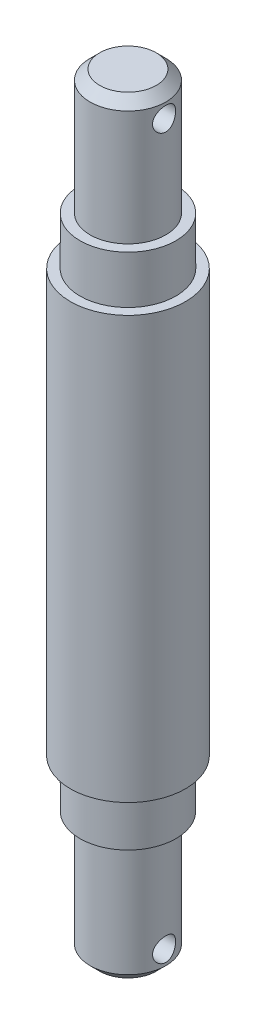
SolidWorks part; units mm, degrees
ref_plane "Plano frontal" through (0, 0, 0) normal (0, 0, 1) x (1, 0, 0)
ref_plane "Plano superior" through (0, 0, 0) normal (0, 1, 0) x (1, 0, 0)
ref_plane "Plano direito" through (0, 0, 0) normal (1, 0, 0) x (0, 0, -1)
sketch "Esboço1" plane through (0, 0, 0) normal (0, 1, 0) x (1, 0, 0)
  circle A0 centre (0, 0) radius 6
  dimension "D1" = 12
extrude "Ressalto-extrusão1" add sketch "Esboço1" along normal blind 44
sketch "Esboço2" plane through (0, 0, 0) normal (0, -1, 0) x (-1, 0, 0)
  circle A0 centre (0, 0) radius 5
  dimension "D1" = 10
extrude "Ressalto-extrusão3" add sketch "Esboço2" against normal blind 49 and the other way blind 5 contours A0
sketch "Esboço3" plane through (0, 49, 0) normal (0, 1, 0) x (1, 0, 0)
  circle A0 centre (0, 0) radius 3.95
  dimension "D1" = 7.9
extrude "Ressalto-extrusão4" add sketch "Esboço3" along normal blind 13 and the other way blind 67
chamfer "Chanfro1" distance 1 angle 45 1 edges at (0, 62, 3.95)
chamfer "Chanfro2" distance 1 angle 45 1 edges at (0, -18, 3.95)
sketch "Esboço5" plane through (0, 0, 0) normal (1, 0, 0) x (0, 0, -1)
  line L0 (2.95, 62) -> (-2.95, 62) construction
  line L1 (0, 61) -> (0, 57.6049) construction
  line L2 (-3.95, 61) -> (3.95, 61) construction
  circle A0 centre (0, 59.5) radius 1.2
  dimension "D1" = 2.4
  dimension "D2" = 2.5
extrude "Corte-extrusão1" cut sketch "Esboço5" against normal through all both and the other way through all
sketch "Esboço6" plane through (0, 0, 0) normal (1, 0, 0) x (0, 0, -1)
  line L0 (0, -21.8279) -> (0, 0) construction
  line L1 (-2.95, -18) -> (2.95, -18) construction
  circle A0 centre (0, -15.5) radius 1.2
  dimension "D1" = 2.4
  dimension "D2" = 2.5
extrude "Corte-extrusão2" cut sketch "Esboço6" against normal through all both and the other way through all
